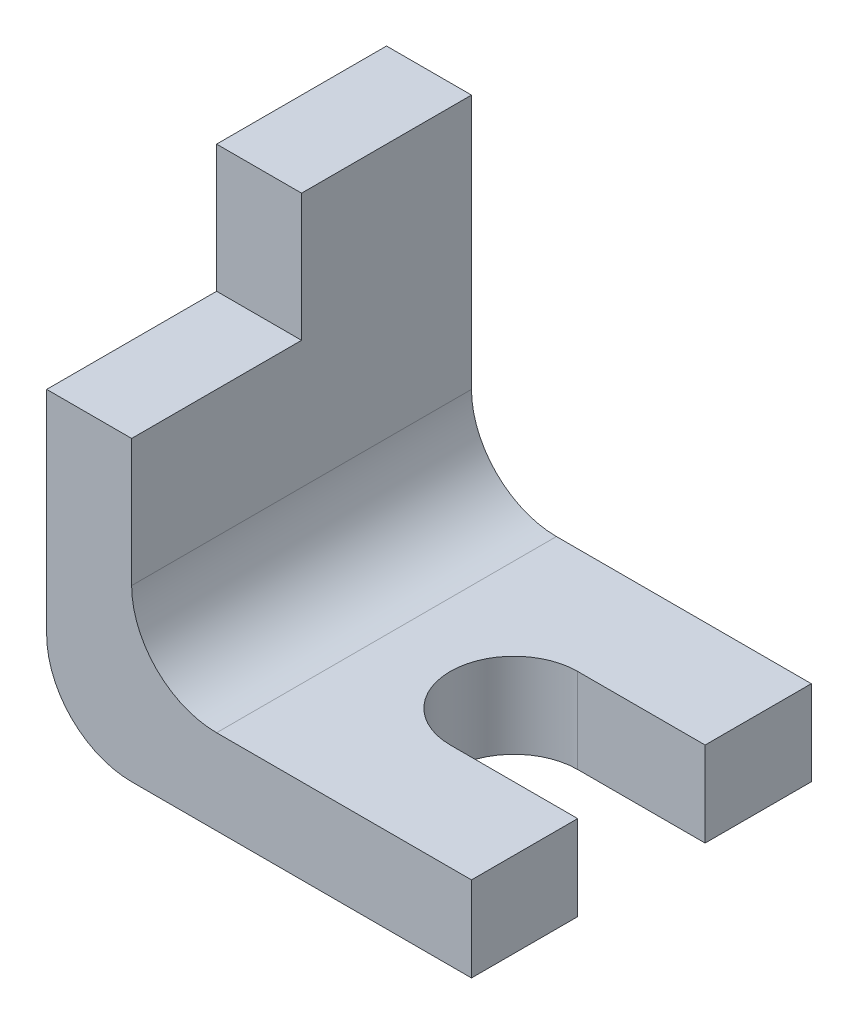
SolidWorks part; units mm, degrees
ref_plane "Front Plane" through (0, 0, 0) normal (0, 0, 1) x (1, 0, 0)
ref_plane "Top Plane" through (0, 0, 0) normal (0, 1, 0) x (1, 0, 0)
ref_plane "Right Plane" through (0, 0, 0) normal (1, 0, 0) x (0, 0, -1)
sketch "Sketch2" plane through (0, 0, 0) normal (0, 0, 1) x (1, 0, 0)
  line L0 (0, 10) -> (0, 50)
  line L1 (10, 0) -> (50, 0)
  line L2 (50, 0) -> (50, 10)
  line L3 (0, 50) -> (10, 50)
  line L4 (10, 20) -> (10, 50)
  line L5 (20, 10) -> (50, 10)
  arc A0 (20, 10) -> (10, 20) centre (20, 20) cw
  arc A1 (0, 10) -> (10, 0) centre (10, 10) ccw
  point P11 (0, 0)
  point P12 (0, 0)
  point P13 (0, 0)
  point P14 (0, 0)
  dimension "D1" = 10
  dimension "D2" = 10
  dimension "D3" = 50
  dimension "D4" = 50
  dimension "D5" = 10
extrude "Boss-Extrude2" add sketch "Sketch2" along normal blind 40 contours L4 L3 L0 A1 L1 L2 L5 A0
sketch "Sketch4" plane through (0, 0, 0) normal (1, 0, 0) x (0, 0, -1)
  line L1 (-40, 50) -> (-20, 50)
  line L2 (-40, 50) -> (-40, 35)
  line L3 (-40, 35) -> (-20, 35)
  line L4 (-20, 50) -> (-20, 35)
  dimension "D1" = 15
  dimension "D2" = 20
extrude "Cut-Extrude1" cut sketch "Sketch4" along normal blind 10
sketch "Sketch5" plane through (0, 0, 0) normal (0, 1, 0) x (1, 0, 0)
  line L0 (50, -20) -> (35, -20)
  line L1 (50, -40) -> (50, 0) construction
  line L2 (35, -20) -> (35, -12.5)
  line L3 (35, -20) -> (35, -27.5)
  line L4 (35, -12.5) -> (50, -12.5)
  line L5 (50, -12.5) -> (50, -27.5)
  line L6 (35, -27.5) -> (50, -27.5)
  circle A0 centre (35, -20) radius 7.5
extrude "Cut-Extrude2" cut sketch "Sketch5" along normal blind 13 contours L2 A0 L3
